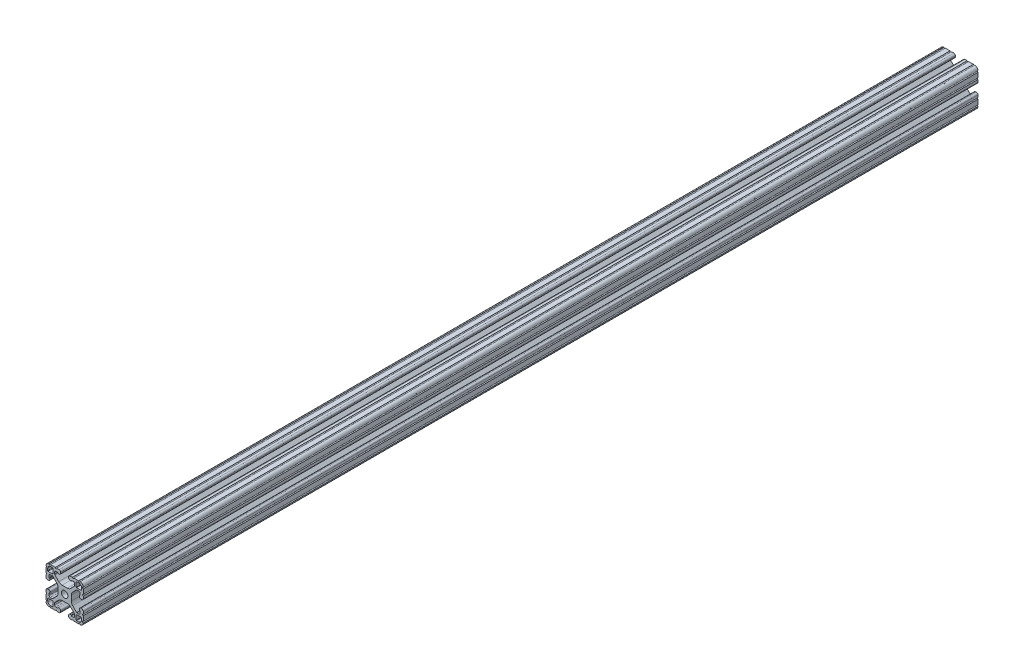
SolidWorks part; units mm, degrees
ref_plane "Front Plane" through (0, 0, 0) normal (0, 0, 1) x (1, 0, 0)
ref_plane "Top Plane" through (0, 0, 0) normal (0, 1, 0) x (1, 0, 0)
ref_plane "Right Plane" through (0, 0, 0) normal (1, 0, 0) x (0, 0, -1)
sketch "Sketch1" plane through (0, 0, 0) normal (0, 0, 1) x (1, 0, 0)
  line L0 (-10.0267, 12.1519) -> (-6.0215, 8.1473)
  line L1 (10.0267, -12.1519) -> (6.0215, -8.1473)
  line L2 (10.287, -14.5547) -> (10.287, -12.7802)
  line L3 (6.8141, -15.8247) -> (9.017, -15.8247)
  line L4 (-10.287, 14.5547) -> (-10.287, 12.7802)
  line L5 (6.8141, -14.986) -> (6.8141, -15.8247)
  line L6 (-6.8141, 15.8247) -> (-9.017, 15.8247)
  line L7 (2.6631, 6.7564) -> (-2.6631, 6.7564)
  line L8 (-6.8141, 14.986) -> (-6.8141, 15.8247)
  line L9 (-5.6388, 14.986) -> (-6.8141, 14.986)
  line L10 (-4.064, 17.4752) -> (-4.064, 16.5608)
  line L11 (-7.9756, 19.05) -> (-5.6388, 19.05)
  line L12 (-14.3256, 19.05) -> (-9.4996, 19.05)
  line L13 (-15.875, 19.05) -> (-15.8496, 19.05)
  line L14 (-19.05, 15.8496) -> (-19.05, 15.875)
  line L15 (-19.05, 9.4996) -> (-19.05, 14.3256)
  line L16 (-19.05, 5.6388) -> (-19.05, 7.9756)
  line L17 (5.6388, -14.986) -> (6.8141, -14.986)
  line L18 (4.064, -17.4752) -> (4.064, -16.5608)
  line L19 (7.9756, -19.05) -> (5.6388, -19.05)
  line L20 (-16.5608, 4.064) -> (-17.4752, 4.064)
  line L21 (14.3256, -19.05) -> (9.4996, -19.05)
  line L22 (-14.986, 6.7506) -> (-14.986, 5.6388)
  line L23 (-15.879, 6.7506) -> (-14.986, 6.7506)
  line L24 (15.875, -19.05) -> (15.8496, -19.05)
  line L25 (19.05, -15.8496) -> (19.05, -15.875)
  line L26 (-15.879, 8.9192) -> (-15.879, 6.7506)
  line L27 (-12.7428, 10.1892) -> (-14.609, 10.1892)
  line L28 (19.05, -9.4996) -> (19.05, -14.3256)
  line L29 (19.05, -5.6388) -> (19.05, -7.9756)
  line L30 (-8.1479, 5.9632) -> (-12.1142, 9.9289)
  line L31 (-16.891, 11.8618) -> (-12.2428, 11.8618)
  line L32 (-11.8618, 12.2428) -> (-11.8618, 16.891)
  line L33 (-12.2428, 17.272) -> (-14.478, 17.272)
  line L34 (-17.272, -14.478) -> (-17.272, -12.2428)
  line L35 (-12.2428, -17.272) -> (-14.478, -17.272)
  line L36 (-11.8618, -12.2428) -> (-11.8618, -16.891)
  line L37 (-16.891, -11.8618) -> (-12.2428, -11.8618)
  line L38 (-17.272, 14.478) -> (-17.272, 12.2428)
  line L39 (16.5608, -4.064) -> (17.4752, -4.064)
  line L40 (14.986, -6.7506) -> (14.986, -5.6388)
  line L41 (15.879, -6.7506) -> (14.986, -6.7506)
  line L42 (15.879, -8.9192) -> (15.879, -6.7506)
  line L43 (12.7428, -10.1892) -> (14.609, -10.1892)
  line L44 (8.1479, -5.9632) -> (12.1142, -9.9289)
  line L45 (6.7564, 2.6043) -> (6.7564, -2.6043)
  line L46 (17.272, 14.478) -> (17.272, 12.2428)
  line L47 (16.891, -11.8618) -> (12.2428, -11.8618)
  line L48 (11.8618, -12.2428) -> (11.8618, -16.891)
  line L49 (12.2428, -17.272) -> (14.478, -17.272)
  line L50 (17.272, -14.478) -> (17.272, -12.2428)
  line L51 (12.2428, 17.272) -> (14.478, 17.272)
  line L52 (11.8618, 12.2428) -> (11.8618, 16.891)
  line L53 (16.891, 11.8618) -> (12.2428, 11.8618)
  line L54 (8.1479, 5.9632) -> (12.1142, 9.9289)
  line L55 (12.7428, 10.1892) -> (14.609, 10.1892)
  line L56 (15.879, 8.9192) -> (15.879, 6.7506)
  line L57 (15.879, 6.7506) -> (14.986, 6.7506)
  line L58 (14.986, 6.7506) -> (14.986, 5.6388)
  line L59 (16.5608, 4.064) -> (17.4752, 4.064)
  line L60 (19.05, 5.6388) -> (19.05, 7.9756)
  line L61 (19.05, 9.4996) -> (19.05, 14.3256)
  line L62 (19.05, 15.8496) -> (19.05, 15.875)
  line L63 (15.875, 19.05) -> (15.8496, 19.05)
  line L64 (14.3256, 19.05) -> (9.4996, 19.05)
  line L65 (7.9756, 19.05) -> (5.6388, 19.05)
  line L66 (4.064, 17.4752) -> (4.064, 16.5608)
  line L67 (5.6388, 14.986) -> (6.8141, 14.986)
  line L68 (6.8141, 14.986) -> (6.8141, 15.8247)
  line L69 (6.8141, 15.8247) -> (9.017, 15.8247)
  line L70 (10.287, 14.5547) -> (10.287, 12.7802)
  line L71 (10.0267, 12.1519) -> (6.0215, 8.1473)
  line L72 (-6.7564, 2.6043) -> (-6.7564, -2.6043)
  line L73 (-8.1479, -5.9632) -> (-12.1142, -9.9289)
  line L74 (-12.7428, -10.1892) -> (-14.609, -10.1892)
  line L75 (-15.879, -8.9192) -> (-15.879, -6.7506)
  line L76 (-15.879, -6.7506) -> (-14.986, -6.7506)
  line L77 (-14.986, -6.7506) -> (-14.986, -5.6388)
  line L78 (-16.5608, -4.064) -> (-17.4752, -4.064)
  line L79 (-19.05, -5.6388) -> (-19.05, -7.9756)
  line L80 (-19.05, -9.4996) -> (-19.05, -14.3256)
  line L81 (-19.05, -15.8496) -> (-19.05, -15.875)
  line L82 (-15.875, -19.05) -> (-15.8496, -19.05)
  line L83 (-14.3256, -19.05) -> (-9.4996, -19.05)
  line L84 (-7.9756, -19.05) -> (-5.6388, -19.05)
  line L85 (-4.064, -17.4752) -> (-4.064, -16.5608)
  line L86 (-5.6388, -14.986) -> (-6.8141, -14.986)
  line L87 (-6.8141, -14.986) -> (-6.8141, -15.8247)
  line L88 (-6.8141, -15.8247) -> (-9.017, -15.8247)
  line L89 (-10.287, -14.5547) -> (-10.287, -12.7802)
  line L90 (-10.0267, -12.1519) -> (-6.0215, -8.1473)
  line L91 (-2.6631, -6.7564) -> (2.6631, -6.7564)
  arc A0 (-10.0267, 12.1519) -> (-10.287, 12.7802) centre (-9.3985, 12.7802) cw
  arc A1 (-19.05, -15.875) -> (-15.875, -19.05) centre (-15.875, -15.875) ccw construction
  arc A2 (-10.287, 14.5547) -> (-9.017, 15.8247) centre (-9.017, 14.5547) cw
  arc A3 (-4.064, 16.5608) -> (-5.6388, 14.986) centre (-5.6388, 16.5608) cw
  arc A4 (10.0267, -12.1519) -> (10.287, -12.7802) centre (9.3985, -12.7802) cw
  arc A5 (10.287, -14.5547) -> (9.017, -15.8247) centre (9.017, -14.5547) cw
  arc A6 (-5.6388, 19.05) -> (-4.064, 17.4752) centre (-5.6388, 17.4752) cw
  arc A7 (-7.9756, 19.05) -> (-9.4996, 19.05) centre (-8.7376, 19.05) cw
  arc A8 (-17.272, -14.478) -> (-14.478, -17.272) centre (-14.478, -14.478) ccw construction
  arc A9 (4.064, -16.5608) -> (5.6388, -14.986) centre (5.6388, -16.5608) cw
  arc A10 (-14.3256, 19.05) -> (-15.8496, 19.05) centre (-15.0876, 19.05) cw
  arc A11 (-19.05, 15.875) -> (-15.875, 19.05) centre (-15.875, 15.875) cw
  arc A12 (-6.0215, 8.1473) -> (-2.6631, 6.7564) centre (-2.6631, 11.5062) ccw
  arc A13 (6.0215, 8.1473) -> (2.6631, 6.7564) centre (2.6631, 11.5062) cw
  arc A14 (-19.05, 15.8496) -> (-19.05, 14.3256) centre (-19.05, 15.0876) cw
  arc A15 (-19.05, 9.4996) -> (-19.05, 7.9756) centre (-19.05, 8.7376) cw
  arc A16 (-17.4752, 4.064) -> (-19.05, 5.6388) centre (-17.4752, 5.6388) cw
  arc A17 (-14.986, 5.6388) -> (-16.5608, 4.064) centre (-16.5608, 5.6388) cw
  arc A18 (-15.879, 8.9192) -> (-14.609, 10.1892) centre (-14.609, 8.9192) cw
  arc A19 (-12.7428, 10.1892) -> (-12.1142, 9.9289) centre (-12.7428, 9.3002) cw
  arc A20 (-16.891, 11.8618) -> (-17.272, 12.2428) centre (-16.891, 12.2428) cw
  arc A21 (5.6388, -19.05) -> (4.064, -17.4752) centre (5.6388, -17.4752) cw
  arc A22 (7.9756, -19.05) -> (9.4996, -19.05) centre (8.7376, -19.05) cw
  arc A23 (14.3256, -19.05) -> (15.8496, -19.05) centre (15.0876, -19.05) cw
  arc A24 (-11.8618, 12.2428) -> (-12.2428, 11.8618) centre (-12.2428, 12.2428) cw
  arc A25 (19.05, -15.875) -> (15.875, -19.05) centre (15.875, -15.875) cw
  arc A26 (-12.2428, 17.272) -> (-11.8618, 16.891) centre (-12.2428, 16.891) cw
  arc A27 (-17.272, 14.478) -> (-14.478, 17.272) centre (-14.478, 14.478) cw
  arc A28 (19.05, -15.8496) -> (19.05, -14.3256) centre (19.05, -15.0876) cw
  arc A29 (19.05, -9.4996) -> (19.05, -7.9756) centre (19.05, -8.7376) cw
  arc A30 (17.4752, -4.064) -> (19.05, -5.6388) centre (17.4752, -5.6388) cw
  arc A31 (14.986, -5.6388) -> (16.5608, -4.064) centre (16.5608, -5.6388) cw
  arc A32 (15.879, -8.9192) -> (14.609, -10.1892) centre (14.609, -8.9192) cw
  arc A33 (12.7428, -10.1892) -> (12.1142, -9.9289) centre (12.7428, -9.3002) cw
  arc A34 (8.1479, -5.9632) -> (6.7564, -2.6043) centre (11.5062, -2.6043) cw
  arc A35 (6.7564, 2.6043) -> (8.1479, 5.9632) centre (11.5062, 2.6043) cw
  arc A36 (16.891, -11.8618) -> (17.272, -12.2428) centre (16.891, -12.2428) cw
  arc A37 (11.8618, -12.2428) -> (12.2428, -11.8618) centre (12.2428, -12.2428) cw
  arc A38 (-17.272, -14.478) -> (-14.478, -17.272) centre (-14.478, -14.478) ccw
  arc A39 (-12.2428, -17.272) -> (-11.8618, -16.891) centre (-12.2428, -16.891) ccw
  arc A40 (-11.8618, -12.2428) -> (-12.2428, -11.8618) centre (-12.2428, -12.2428) ccw
  arc A41 (-16.891, -11.8618) -> (-17.272, -12.2428) centre (-16.891, -12.2428) ccw
  arc A42 (12.2428, -17.272) -> (11.8618, -16.891) centre (12.2428, -16.891) cw
  circle A43 centre (0, 0) radius 3.3274
  arc A44 (17.272, -14.478) -> (14.478, -17.272) centre (14.478, -14.478) cw
  arc A45 (17.272, 14.478) -> (14.478, 17.272) centre (14.478, 14.478) ccw
  arc A46 (12.2428, 17.272) -> (11.8618, 16.891) centre (12.2428, 16.891) ccw
  arc A47 (11.8618, 12.2428) -> (12.2428, 11.8618) centre (12.2428, 12.2428) ccw
  arc A48 (16.891, 11.8618) -> (17.272, 12.2428) centre (16.891, 12.2428) ccw
  arc A49 (12.7428, 10.1892) -> (12.1142, 9.9289) centre (12.7428, 9.3002) ccw
  arc A50 (15.879, 8.9192) -> (14.609, 10.1892) centre (14.609, 8.9192) ccw
  arc A51 (14.986, 5.6388) -> (16.5608, 4.064) centre (16.5608, 5.6388) ccw
  arc A52 (17.4752, 4.064) -> (19.05, 5.6388) centre (17.4752, 5.6388) ccw
  arc A53 (19.05, 9.4996) -> (19.05, 7.9756) centre (19.05, 8.7376) ccw
  arc A54 (19.05, 15.8496) -> (19.05, 14.3256) centre (19.05, 15.0876) ccw
  arc A55 (19.05, 15.875) -> (15.875, 19.05) centre (15.875, 15.875) ccw
  arc A56 (14.3256, 19.05) -> (15.8496, 19.05) centre (15.0876, 19.05) ccw
  arc A57 (7.9756, 19.05) -> (9.4996, 19.05) centre (8.7376, 19.05) ccw
  arc A58 (5.6388, 19.05) -> (4.064, 17.4752) centre (5.6388, 17.4752) ccw
  arc A59 (4.064, 16.5608) -> (5.6388, 14.986) centre (5.6388, 16.5608) ccw
  arc A60 (10.287, 14.5547) -> (9.017, 15.8247) centre (9.017, 14.5547) ccw
  arc A61 (10.0267, 12.1519) -> (10.287, 12.7802) centre (9.3985, 12.7802) ccw
  arc A62 (-6.7564, 2.6043) -> (-8.1479, 5.9632) centre (-11.5062, 2.6043) ccw
  arc A63 (-8.1479, -5.9632) -> (-6.7564, -2.6043) centre (-11.5062, -2.6043) ccw
  arc A64 (-12.7428, -10.1892) -> (-12.1142, -9.9289) centre (-12.7428, -9.3002) ccw
  arc A65 (-15.879, -8.9192) -> (-14.609, -10.1892) centre (-14.609, -8.9192) ccw
  arc A66 (-14.986, -5.6388) -> (-16.5608, -4.064) centre (-16.5608, -5.6388) ccw
  arc A67 (-17.4752, -4.064) -> (-19.05, -5.6388) centre (-17.4752, -5.6388) ccw
  arc A68 (-19.05, -9.4996) -> (-19.05, -7.9756) centre (-19.05, -8.7376) ccw
  arc A69 (-19.05, -15.8496) -> (-19.05, -14.3256) centre (-19.05, -15.0876) ccw
  arc A70 (-19.05, -15.875) -> (-15.875, -19.05) centre (-15.875, -15.875) ccw
  arc A71 (-14.3256, -19.05) -> (-15.8496, -19.05) centre (-15.0876, -19.05) ccw
  arc A72 (-7.9756, -19.05) -> (-9.4996, -19.05) centre (-8.7376, -19.05) ccw
  arc A73 (-5.6388, -19.05) -> (-4.064, -17.4752) centre (-5.6388, -17.4752) ccw
  arc A74 (-4.064, -16.5608) -> (-5.6388, -14.986) centre (-5.6388, -16.5608) ccw
  arc A75 (-10.287, -14.5547) -> (-9.017, -15.8247) centre (-9.017, -14.5547) ccw
  arc A76 (-10.0267, -12.1519) -> (-10.287, -12.7802) centre (-9.3985, -12.7802) ccw
  arc A77 (-2.6631, -6.7564) -> (-6.0215, -8.1473) centre (-2.6631, -11.5062) ccw
  arc A78 (6.0215, -8.1473) -> (2.6631, -6.7564) centre (2.6631, -11.5062) ccw
  point P134 (0, 0)
extrude "Boss-Extrude1" add sketch "Sketch1" along normal mid plane 914.4
